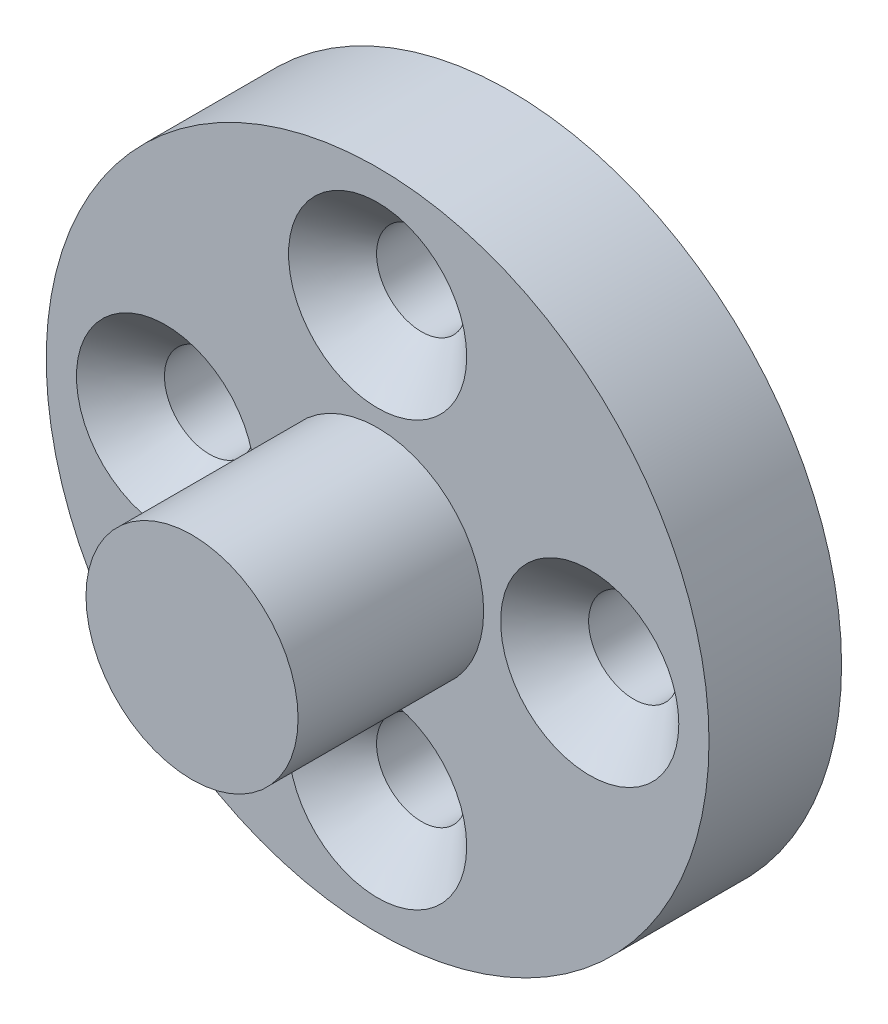
SolidWorks part; units mm, degrees
ref_plane "Plano frontal" through (0, 0, 0) normal (0, 0, 1) x (1, 0, 0)
ref_plane "Plano superior" through (0, 0, 0) normal (0, 1, 0) x (1, 0, 0)
ref_plane "Plano direito" through (0, 0, 0) normal (1, 0, 0) x (0, 0, -1)
sketch "Esboço2" plane through (0, 0, 0) normal (0, 0, 1) x (1, 0, 0)
  circle A0 centre (0, 0) radius 12.5
  dimension "D1" = 25
extrude "Ressalto-extrusão1" add sketch "Esboço2" along normal blind 5
sketch "Esboço3" plane through (0, 0, 5) normal (0, 0, 1) x (1, 0, 0)
  circle A0 centre (0, 0) radius 4
  dimension "D1" = 8
extrude "Ressalto-extrusão2" add sketch "Esboço3" along normal blind 7
hole_wizard "Escareado para parafuso Allen sextavado escareado de M31" positions "Esboço4" profile "Esboço5" countersink size "M3" standard "ISO" end condition through all
sketch "Esboço4" plane through (0, 0, 5) normal (0, 0, 1) x (1, 0, 0)
  line L0 (0, 0) -> (0, 8) construction
  point P0 (0, 8)
  point P11 (8, 0)
  point P12 (0, -8)
  point P13 (-8, 0)
  dimension "D1" = 8
  dimension "D2" = 4
sketch "Esboço5" plane through (0, 8, 5) normal (1, 0, 0) x (0, -1, 0)
  line L0 (0, 0) -> (0, 5)
  line L1 (0, 5) -> (1.7, 5)
  line L2 (1.7, 5) -> (1.7, 1.66)
  line L3 (1.7, 1.66) -> (3.36, 0)
  line L5 (3.36, 0) -> (0, 0)
  line L6 (-1.7, 1.66) -> (-3.36, 0) construction
  line L11 (0, -6.35) -> (0, 107.95) construction
  dimension "Thru Hole Dia." = 3.4
  dimension "Thru Hole Depth" = 5
  dimension "Near C'Sink Dia." = 6.72
  dimension "Near C'Sink Angle" = 90
